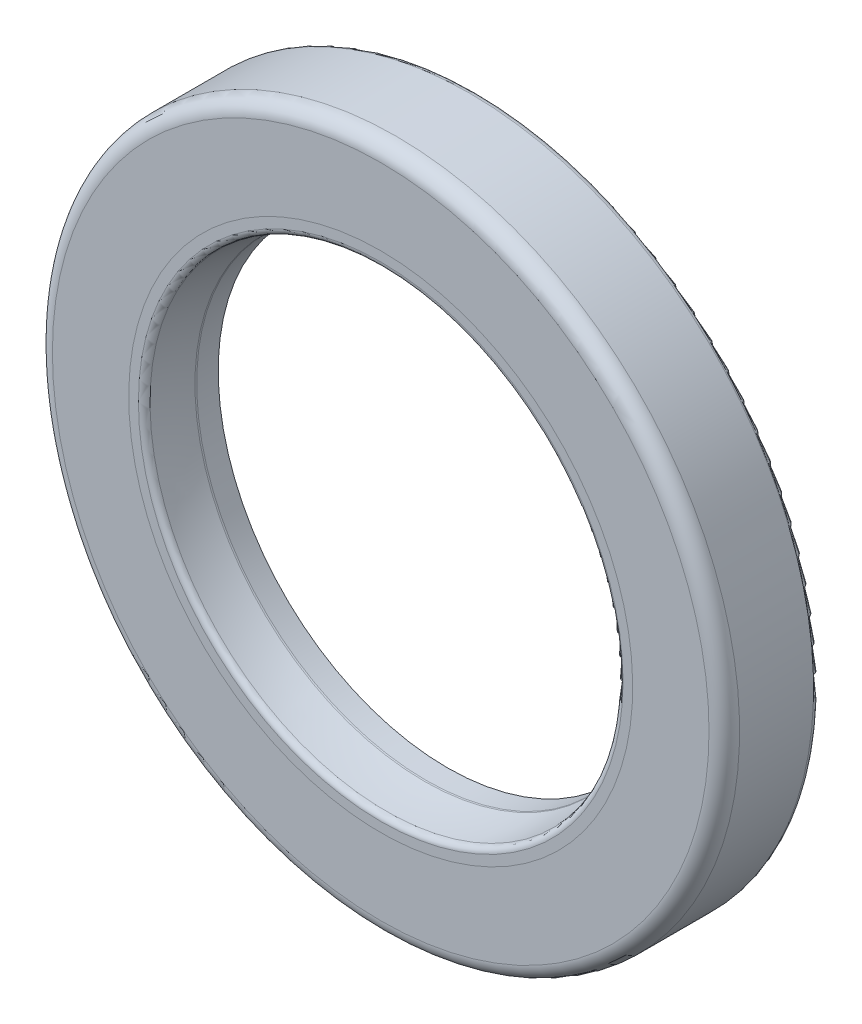
SolidWorks part; units mm, degrees
material "Rubber"
ref_plane "Front Plane" through (0, 0, 0) normal (0, 0, 1) x (1, 0, 0)
ref_plane "Top Plane" through (0, 0, 0) normal (0, 1, 0) x (1, 0, 0)
ref_plane "Right Plane" through (0, 0, 0) normal (1, 0, 0) x (0, 0, -1)
sketch "Sketch1" plane through (0, 0, 0) normal (1, 0, 0) x (0, 0, -1)
  line L0 (-1.5367, 14.2748) -> (1.5367, 14.2748) construction
  line L1 (-2.1717, -13.6398) -> (-2.1717, 13.6398) construction
  line L2 (1.7907, 14.0208) -> (1.7907, 13.5128) construction
  line L3 (1.7907, 13.5128) -> (1.5367, 13.5128) construction
  line L4 (1.5367, 13.5128) -> (1.5367, 13.7668) construction
  line L5 (1.0287, 13.7668) -> (-1.6637, 13.7668) construction
  line L6 (-1.6637, 13.7668) -> (-1.6637, 0) construction
  line L7 (-1.6637, 0) -> (-2.1717, 0) construction
  line L8 (-1.6637, 13.7668) -> (-1.6637, 14.2748) construction
  line L9 (-1.6637, 13.7668) -> (-2.1717, 13.7668) construction
  line L10 (-1.6637, 10.8312) -> (0.602, 10.4521) construction
  line L11 (0.602, 10.4521) -> (0.602, 9.525) construction
  line L12 (-0.3251, 9.525) -> (-1.6637, 9.749) construction
  line L13 (-1.6637, 9.749) -> (-2.1717, 9.834) construction
  line L14 (-2.1717, 9.834) -> (-2.1717, 10.469) construction
  line L15 (-2.1717, 10.469) -> (-1.6637, 10.469) construction
  line L17 (0.602, 9.525) -> (-0.3251, 9.525) construction
  arc A0 (1.5367, 13.7668) -> (1.0287, 13.7668) centre (1.2827, 13.7668) ccw construction
  arc A1 (1.5367, 14.2748) -> (1.7907, 14.0208) centre (1.5367, 14.0208) cw construction
  arc A2 (-1.5367, 14.2748) -> (-2.1717, 13.6398) centre (-1.5367, 13.6398) ccw construction
  circle A3 centre (-1.6002, 13.7033) radius 0.0635 construction
  arc A4 (-0.3251, 9.525) -> (-2.1717, 9.834) centre (-2.9182, -0.2985) ccw construction
  arc A5 (-1.6637, 10.8312) -> (0.602, 10.4521) centre (-3.6693, -8.1129) cw construction
  point P0 (0, 0)
  point P3 (0, 14.2748)
  point P6 (-2.1717, 0)
  point P20 (1.7907, 14.2748)
  point P23 (-2.1717, 14.2748)
  dimension "D3" = 0.254
  dimension "D4" = 0.254
  dimension "D5" = 0.635
  dimension "D9" = 0.127
  dimension "D11" = 10.16
  dimension "D12" = 19.05
  dimension "Seal OD" = 28.5496
  dimension "Seal Width" = 3.9624
  dimension "D1" = 0.508
  dimension "D2" = 0.254
  dimension "Seal ID" = 19.05
  dimension "D6" = 0.9271
  dimension "D7" = 80.5
  dimension "D8" = 2.7737
  dimension "D10" = 0.635
sketch "Sketch2" plane through (0, 0, 0) normal (1, 0, 0) x (0, 0, -1)
  line L8 (-2.1717, 10.469) -> (-2.1717, 13.6398)
  line L9 (-1.5367, 14.2748) -> (1.5367, 14.2748)
  line L10 (1.7907, 14.0208) -> (1.7907, 13.5128)
  line L11 (1.7907, 13.5128) -> (1.5367, 13.5128)
  line L12 (1.5367, 13.5128) -> (1.5367, 13.7668)
  line L13 (1.0287, 13.7668) -> (-1.6002, 13.7668)
  line L14 (-1.6637, 13.7033) -> (-1.6637, 10.469)
  line L15 (-1.6637, 10.469) -> (-2.1717, 10.469)
  arc A7 (-2.1717, 13.6398) -> (-1.5367, 14.2748) centre (-1.5367, 13.6398) cw
  arc A8 (1.5367, 14.2748) -> (1.7907, 14.0208) centre (1.5367, 14.0208) cw
  arc A9 (1.5367, 13.7668) -> (1.0287, 13.7668) centre (1.2827, 13.7668) ccw
  circle A10 centre (-1.6002, 13.7033) radius 0.0635 construction
  arc A11 (-1.6002, 13.7668) -> (-1.6637, 13.7033) centre (-1.6002, 13.7033) ccw
revolve "Revolve1" add sketch "Sketch2" angle 360 about L7
sketch "Sketch3" plane through (0, 0, 0) normal (1, 0, 0) x (0, 0, -1)
  line L0 (0.602, 9.525) -> (-0.3251, 9.525) construction
  line L1 (0.602, 10.4521) -> (0.602, 9.525) construction
  line L2 (0.602, 9.525) -> (-0.2924, 9.525)
  line L3 (0.602, 10.2488) -> (0.602, 9.525)
  line L4 (-2.1717, 10.0673) -> (-2.1717, 10.469)
  line L5 (-2.1717, 10.469) -> (-1.6637, 10.469)
  line L6 (-1.6637, 10.469) -> (-1.6637, 10.8312)
  arc A0 (0.602, 10.4521) -> (-1.6637, 10.8312) centre (-3.6693, -8.1129) ccw construction
  arc A1 (-0.3251, 9.525) -> (-2.1717, 9.834) centre (-2.9182, -0.2985) ccw construction
  arc A2 (0.4023, 10.4969) -> (-1.6637, 10.8312) centre (-3.6693, -8.1129) ccw
  arc A3 (-0.3564, 9.5332) -> (-1.9421, 9.8145) centre (-2.9182, -0.2985) ccw
  arc A4 (-0.3564, 9.5332) -> (-0.2924, 9.525) centre (-0.2924, 9.779) ccw
  arc A5 (-1.9421, 9.8145) -> (-2.1717, 10.0673) centre (-1.9177, 10.0673) cw
  arc A6 (0.4023, 10.4969) -> (0.602, 10.2488) centre (0.348, 10.2488) cw
  dimension "D1" = 0.254
revolve "Revolve2" add sketch "Sketch3" angle 360 about L7
equation "\"D2@Sketch1\"=\"D1@Sketch1\"/2"
equation "\"D3@Sketch1\"=\"D2@Sketch1\""
equation "\"D8@Sketch1\"=\"Seal Width@Sketch1\"*.7"
equation "\"D9@Sketch1\"=\"D5@Sketch1\"-\"D1@Sketch1\""
